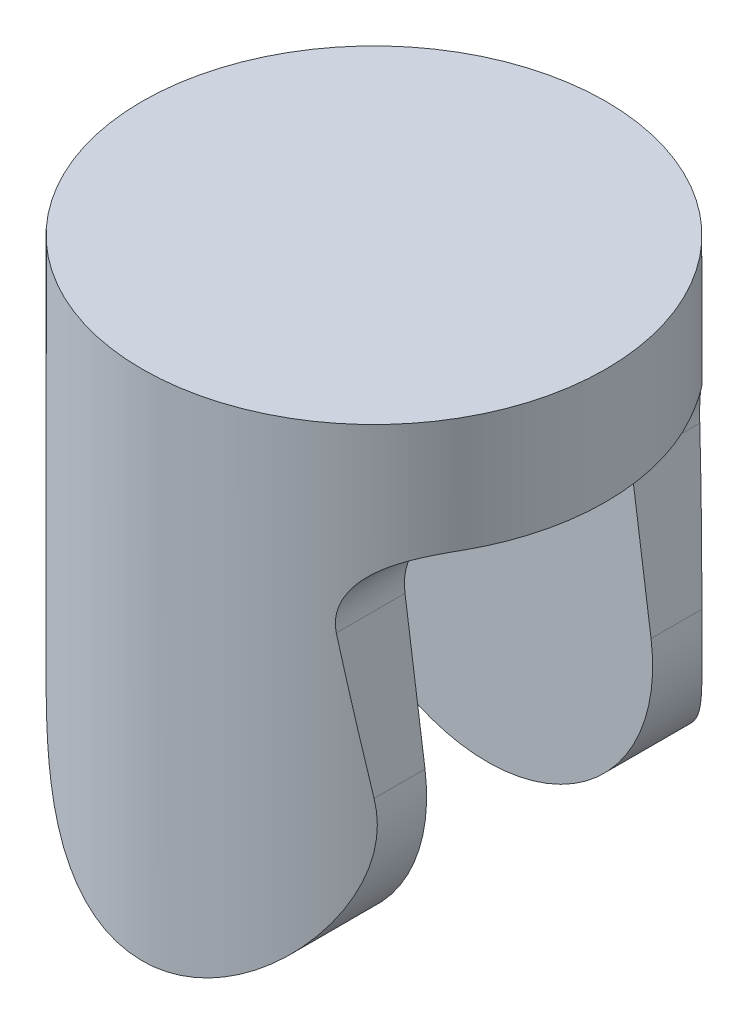
SolidWorks part; units mm, degrees
ref_plane "Front Plane" through (0, 0, 0) normal (0, 0, 1) x (1, 0, 0)
ref_plane "Top Plane" through (0, 0, 0) normal (0, 1, 0) x (1, 0, 0)
ref_plane "Right Plane" through (0, 0, 0) normal (1, 0, 0) x (0, 0, -1)
sketch "Sketch1" plane through (0, 0, 0) normal (0, 1, 0) x (1, 0, 0)
  circle A0 centre (0, 0) radius 119
  dimension "D1" = 238
extrude "Boss-Extrude1" add sketch "Sketch1" along normal blind 59
ref_plane "Plane1" through (58, 0, 0) normal (1, 0, 0) x (0, 0, -1)
sketch "Sketch2" plane through (58, 0, 0) normal (1, 0, 0) x (0, 0, -1)
  line L0 (-69.111, 59) -> (-84.1728, 166.1703)
  line L1 (119, 59) -> (-119, 59) construction
  line L2 (84.7929, 183.9293) -> (93.5289, 59)
  line L3 (-69.111, 59) -> (93.5289, 59)
  arc A0 (84.7929, 183.9293) -> (-84.1728, 166.1703) centre (0, 178) ccw
  dimension "D1" = 98
  dimension "D3" = 170
  dimension "D2" = 178
  dimension "D4" = 86
extrude "Boss-Extrude2" add sketch "Sketch2" along normal up to surface (26.1186 mm away)
fillet "Fillet1" radius 30 1 edges at (77.4373, 59, 69.111)
fillet "Fillet2" radius 10 1 edges at (65.7877, 59, -93.5289)
mirror "Mirror1" about plane through (0, 0, 0) normal (1, 0, 0) of "Boss-Extrude2", "Fillet1", "Fillet2"
sketch "Sketch3" plane through (0, 0, 0) normal (1, 0, 0) x (0, 0, -1)
  point P0 (0, 178)
move or copy body "Body-Move/Copy1" bodies to move or copy 103 copy no translate (0, -178, 0) parameters "D1"=0, "D2"=0, "D3"=0
move or copy body "Body-Move/Copy2" bodies to move or copy 104 copy no rotation origin (0, 0, 0) rotation axis (0.7071, 0, 0.7071) rotation angle 180
